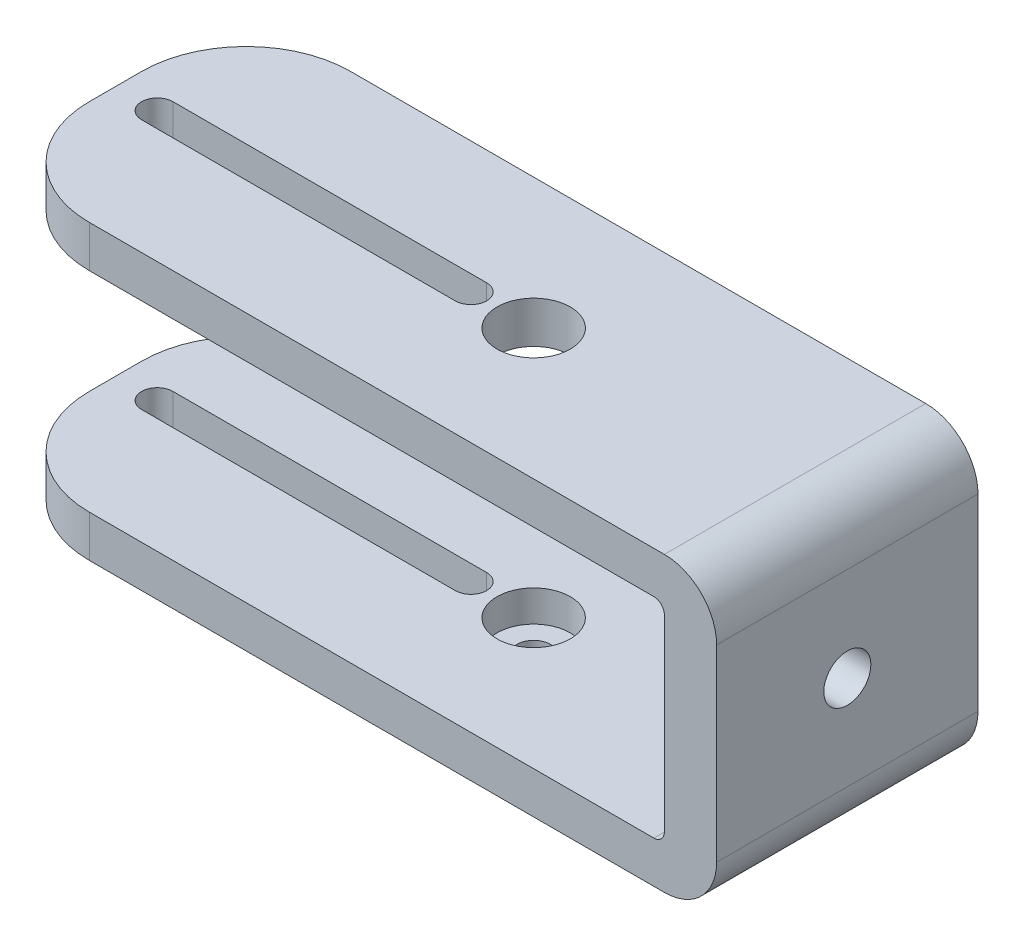
SolidWorks part; units mm, degrees
ref_plane "Спереди" through (0, 0, 0) normal (0, 0, 1) x (1, 0, 0)
ref_plane "Сверху" through (0, 0, 0) normal (0, 1, 0) x (1, 0, 0)
ref_plane "Справа" through (0, 0, 0) normal (1, 0, 0) x (0, 0, -1)
sketch "Эскиз1" plane through (0, 0, 0) normal (0, 1, 0) x (1, 0, 0)
  line L1 (-35, 12.5) -> (35, 12.5)
  line L2 (-35, 12.5) -> (-35, -12.5)
  line L3 (-35, -12.5) -> (35, -12.5)
  line L4 (35, 12.5) -> (35, -12.5)
  line L5 (-35, 12.5) -> (35, -12.5) construction
  line L6 (-35, -12.5) -> (35, 12.5) construction
  point P0 (0, 0)
  dimension "D1" = 25
  dimension "D2" = 70
extrude "Бобышка-Вытянуть1" add sketch "Эскиз1" along normal blind 4
sketch "Эскиз2" plane through (0, 4, 0) normal (0, 1, 0) x (1, 0, 0)
  line L0 (-35, -12.5) -> (35, -12.5) construction
  line L1 (35, 12.5) -> (30, 12.5)
  line L2 (35, 12.5) -> (35, -12.5)
  line L3 (35, -12.5) -> (30, -12.5)
  line L4 (30, 12.5) -> (30, -12.5)
  dimension "D1" = 5
extrude "Бобышка-Вытянуть2" add sketch "Эскиз2" along normal blind 20
sketch "Эскиз3" plane through (0, 24, 0) normal (0, 1, 0) x (1, 0, 0)
  line L1 (35, 12.5) -> (-35, 12.5)
  line L2 (35, 12.5) -> (35, -12.5)
  line L3 (35, -12.5) -> (-35, -12.5)
  line L4 (-35, 12.5) -> (-35, -12.5)
extrude "Бобышка-Вытянуть3" add sketch "Эскиз3" along normal blind 4
sketch "Эскиз4" plane through (0, 0, 0) normal (0, -1, 0) x (1, 0, 0)
  line L0 (-35, 0) -> (5, 0) construction
  line L1 (-35, -12.5) -> (-35, 12.5) construction
  circle A0 centre (5, 0) radius 1.6
  dimension "D1" = 3.2
  dimension "D2" = 40
extrude "Вырез-Вытянуть1" cut sketch "Эскиз4" against normal blind 4
sketch "Эскиз5" plane through (0, 4, 0) normal (0, 1, 0) x (1, 0, 0)
  circle A0 centre (5, 0) radius 3.5
  dimension "D1" = 7
extrude "Вырез-Вытянуть2" cut sketch "Эскиз5" against normal blind 3
sketch "Эскиз6" plane through (0, 24, 0) normal (0, -1, 0) x (1, 0, 0)
  circle A0 centre (5, 0) radius 3.5
  dimension "D1" = 7
extrude "Вырез-Вытянуть3" cut sketch "Эскиз6" against normal through all
sketch "Эскиз7" plane through (0, 28, 0) normal (0, 1, 0) x (1, 0, 0)
  line L0 (-31, 0) -> (-1, 0) construction
  line L1 (-31, 1.5) -> (-1, 1.5)
  line L2 (-31, -1.5) -> (-1, -1.5)
  line L3 (-1, 0) -> (35, 0) construction
  line L4 (35, -12.5) -> (35, 12.5) construction
  line L5 (-35, 12.5) -> (-35, -12.5) construction
  arc A0 (-31, 1.5) -> (-31, -1.5) centre (-31, 0) ccw
  arc A1 (-1, -1.5) -> (-1, 1.5) centre (-1, 0) ccw
  point P3 (-16, 0)
  dimension "D1" = 3
  dimension "D2" = 30
  dimension "D3" = 4
extrude "Вырез-Вытянуть4" cut sketch "Эскиз7" against normal through all
fillet "Скругление1" radius 10 4 edges at (-35, 26, 12.5) (-35, 2, 12.5) (-35, 2, -12.5) (-35, 26, -12.5)
sketch "Эскиз8" plane through (35, 0, 0) normal (1, 0, 0) x (0, 0, -1)
  line L0 (-12.5, 14) -> (12.5, 14) construction
  line L1 (-12.5, 28) -> (-12.5, 0) construction
  line L2 (12.5, 28) -> (12.5, 0) construction
  circle A0 centre (0, 14) radius 2.25
  dimension "D1" = 4.5
extrude "Вырез-Вытянуть5" cut sketch "Эскиз8" against normal through all
fillet "Скругление2" radius 1 2 edges at (30, 24, 0) (30, 4, 0)
fillet "Скругление3" radius 5 2 edges at (35, 0, 0) (35, 28, 0)
